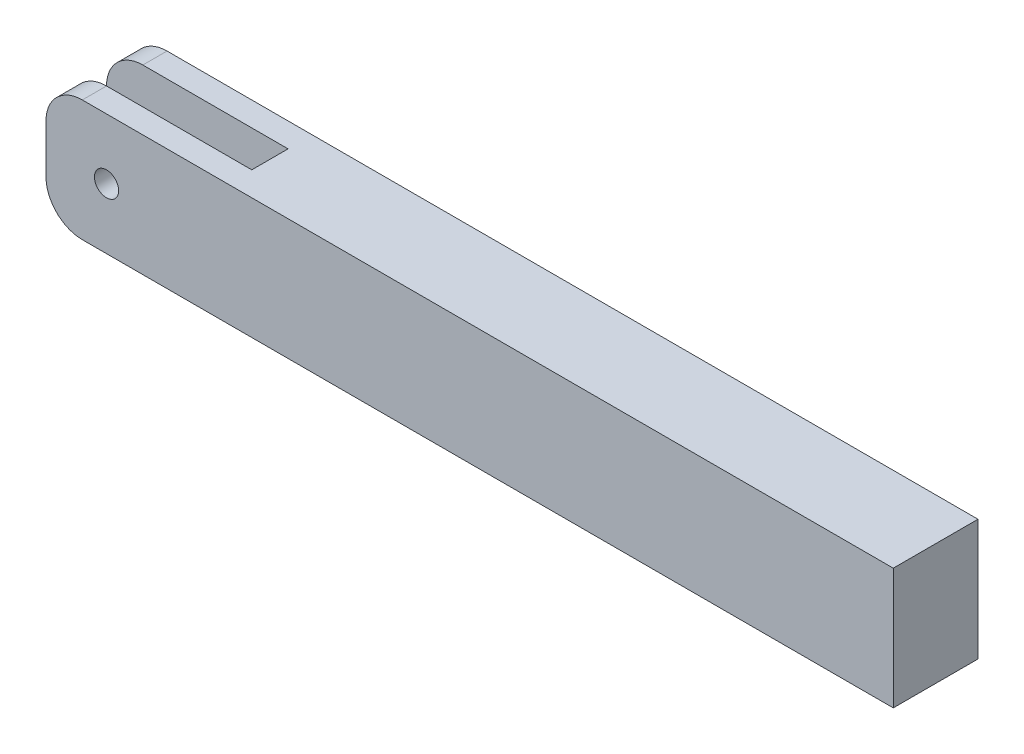
SolidWorks part; units mm, degrees
ref_plane "Front" through (0, 0, 0) normal (0, 0, 1) x (1, 0, 0)
ref_plane "Top" through (0, 0, 0) normal (0, 1, 0) x (1, 0, 0)
ref_plane "Right" through (0, 0, 0) normal (1, 0, 0) x (0, 0, -1)
other "Configuration Table"
sketch "Sketch1" plane through (0, 0, 0) normal (0, 0, 1) x (1, 0, 0)
  line L1 (-10, 25) -> (325, 25)
  line L2 (-25, 10) -> (-25, -10)
  line L3 (-10, -25) -> (325, -25)
  line L4 (325, 25) -> (325, -25)
  arc A1 (-10, -25) -> (-25, -10) centre (-10, -10) cw
  arc A2 (-10, 25) -> (-25, 10) centre (-10, 10) ccw
  dimension "D6" = 15
  dimension "D1" = 50
  dimension "D2" = 350
  dimension "D3" = 25
  dimension "D4" = 25
extrude "Extrude1" add sketch "Sketch1" along normal mid plane 35
sketch "Sketch2" plane through (0, 25, 0) normal (0, 1, 0) x (-1, 0, 0)
  line L0 (25, 17.5) -> (25, -17.5) construction
  line L1 (25, -7.5) -> (-50, -7.5)
  line L2 (25, -7.5) -> (25, 7.5)
  line L3 (25, 7.5) -> (-50, 7.5)
  line L4 (-50, -7.5) -> (-50, 7.5)
  point P6 (25, 0)
  dimension "D1" = 75
  dimension "D2" = 15
extrude "Cut-Extrude1" cut sketch "Sketch2" against normal through all
sketch "Sketch3" plane through (0, 0, 0) normal (0, 0, 1) x (1, 0, 0)
  circle A0 centre (0, 0) radius 5
  dimension "D1" = 10
extrude "Cut-Extrude2" cut sketch "Sketch3" against normal through all and the other way through all
